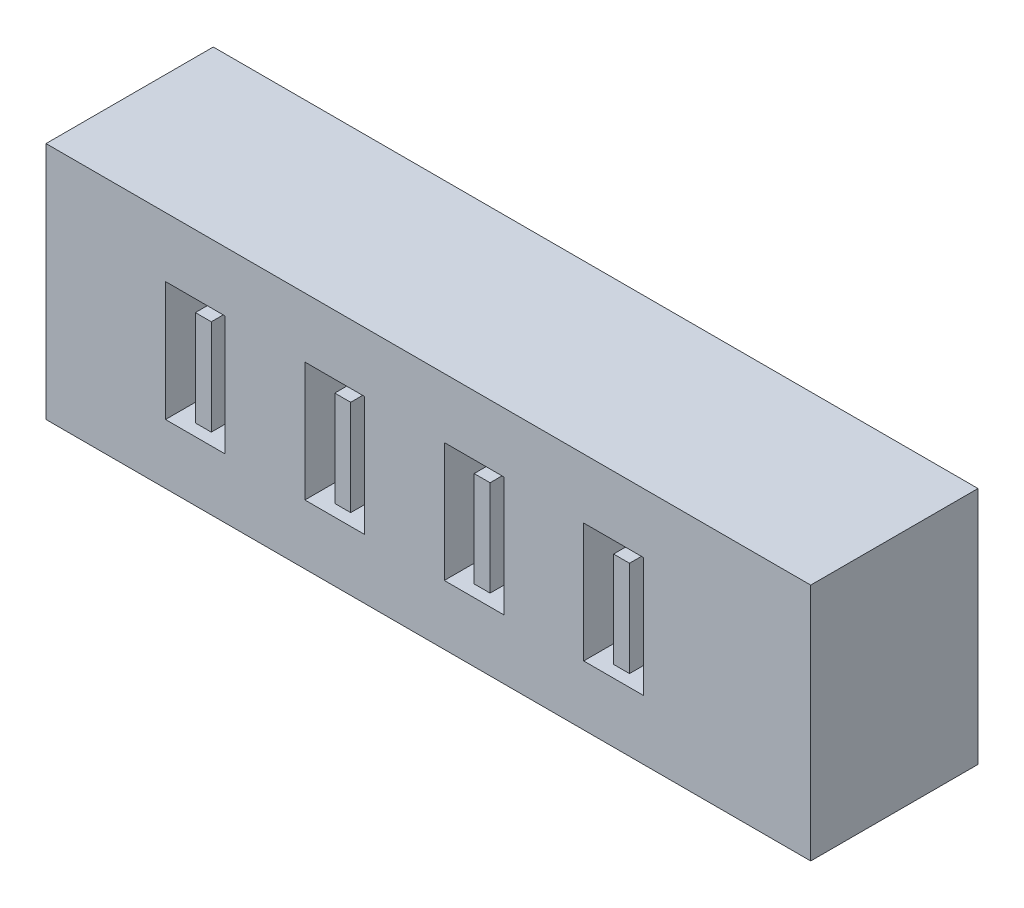
SolidWorks part; units mm, degrees
ref_plane "Plan de face" through (0, 0, 0) normal (0, 0, 1) x (1, 0, 0)
ref_plane "Plan de dessus" through (0, 0, 0) normal (0, 1, 0) x (1, 0, 0)
ref_plane "Plan de droite" through (0, 0, 0) normal (1, 0, 0) x (0, 0, -1)
sketch "Esquisse1" plane through (0, 0, 0) normal (0, 0, 1) x (1, 0, 0)
  line L1 (-33.9359, 14.7668) -> (62.0641, 14.7668)
  line L2 (-33.9359, 14.7668) -> (-33.9359, -15.2332)
  line L3 (-33.9359, -15.2332) -> (62.0641, -15.2332)
  line L4 (62.0641, 14.7668) -> (62.0641, -15.2332)
  dimension "D1" = 30
  dimension "D2" = 96
extrude "Boss.-Extru.1" add sketch "Esquisse1" along normal blind 21
sketch "Esquisse2" plane through (0, 0, 21) normal (0, 0, 1) x (1, 0, 0)
  line L0 (-18.9359, -7.7332) -> (-11.4359, -7.7332)
  line L1 (-18.9359, -7.7332) -> (-18.9359, 7.2668)
  line L2 (-18.9359, 7.2668) -> (-11.4359, 7.2668)
  line L3 (-11.4359, -7.7332) -> (-11.4359, 7.2668)
  line L4 (-15.1859, -6.2332) -> (-13.1859, -6.2332)
  line L5 (-15.1859, -6.2332) -> (-15.1859, 5.7668)
  line L6 (-15.1859, 5.7668) -> (-13.1859, 5.7668)
  line L7 (-13.1859, -6.2332) -> (-13.1859, 5.7668)
  line L8 (-33.9359, 14.7668) -> (-33.9359, -15.2332) construction
  point P4 (-18.9359, -0.2332)
  point P9 (-15.1859, -0.2332)
  point P12 (-33.9359, -0.2332)
  dimension "D1" = 15
  dimension "D2" = 7.5
  dimension "D3" = 2
  dimension "D4" = 12
  dimension "D5" = 1.75
  dimension "D6" = 15
extrude "Enlèv. mat.-Extru.1" cut sketch "Esquisse2" against normal blind 12
pattern_linear "Répétition linéaire1" count 4 spacing 17.5 along (1, 0, 0) of "Enlèv. mat.-Extru.1"
